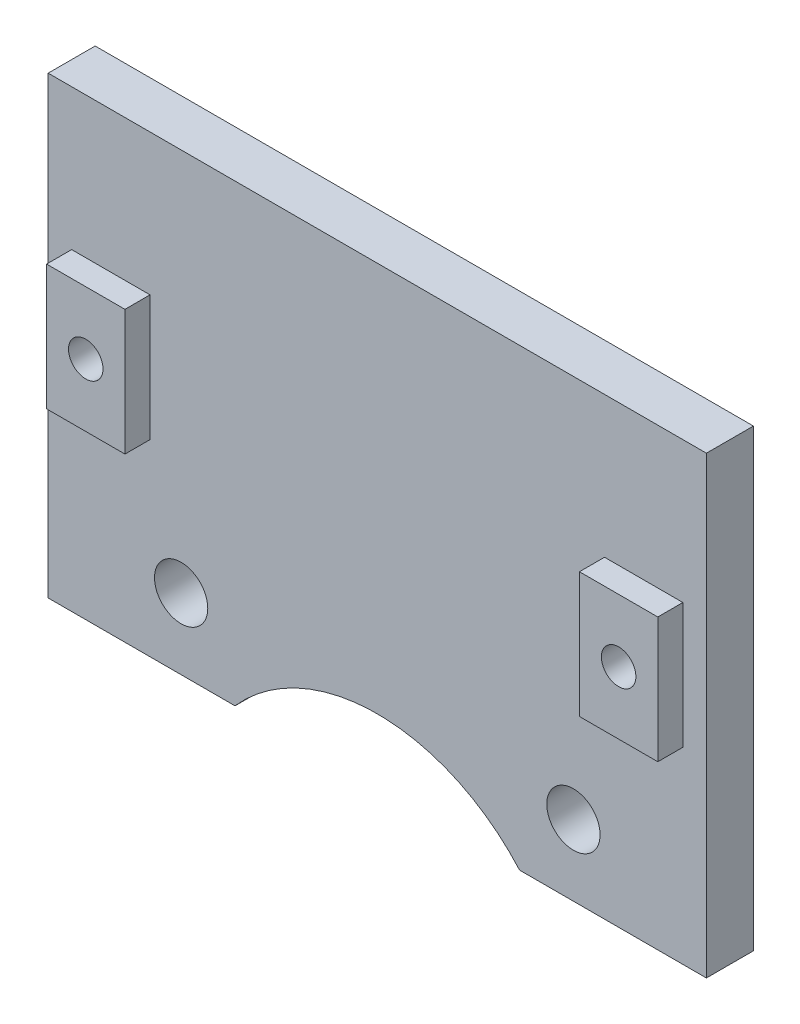
SolidWorks part; units mm, degrees
other "Carrier Accelerometer Bracket"
ref_plane "Front Plane" through (0, 0, 0) normal (0, 0, 1) x (1, 0, 0)
ref_plane "Top Plane" through (0, 0, 0) normal (0, 1, 0) x (1, 0, 0)
ref_plane "Right Plane" through (0, 0, 0) normal (1, 0, 0) x (0, 0, -1)
sketch3d "Mounting Plate Sketch datum points"
  point P0 (0, 0, 0)
  point P1 (10, 0, 0)
  point P2 (0, 10, 0)
ref_plane "Mounting Plate Sketch plane" through (0, 0, 0) normal (0, 0, 1) x (1, 0, 0)
sketch "Mounting Plate Sketch" plane through (0, 0, 0) normal (0, 0, 1) x (1, 0, 0)
  line L0 (-21, -16) -> (21, -16)
  line L1 (21, -16) -> (21, 13)
  line L2 (21, 13) -> (-21, 13)
  line L3 (-21, 13) -> (-21, -16)
extrude "Mounting Plate" add sketch "Mounting Plate Sketch" along normal blind 3 separate body
sketch3d "Axle Collar Clearance Sketch datum points"
  point P0 (0, 0, -0.1)
  point P1 (10, 0, -0.1)
  point P2 (0, 10, -0.1)
ref_plane "Axle Collar Clearance Sketch plane" through (0, 0, -0.1) normal (0, 0, 1) x (1, 0, 0)
sketch "Axle Collar Clearance Sketch" plane through (0, 0, -0.1) normal (0, 0, 1) x (1, 0, 0)
  circle A0 centre (0, -24) radius 12.1
extrude "Axle Collar Clearance" cut sketch "Axle Collar Clearance Sketch" along normal blind 3.2
sketch3d "M3 Cap Bolt Hole 1 Sketch datum points"
  point P0 (0, 0, -0.1)
  point P1 (10, 0, -0.1)
  point P2 (0, 10, -0.1)
ref_plane "M3 Cap Bolt Hole 1 Sketch plane" through (0, 0, -0.1) normal (0, 0, 1) x (1, 0, 0)
sketch "M3 Cap Bolt Hole 1 Sketch" plane through (0, 0, -0.1) normal (0, 0, 1) x (1, 0, 0)
  circle A0 centre (-12.5158, -11.4842) radius 1.7
extrude "M3 Cap Bolt Hole 1" cut sketch "M3 Cap Bolt Hole 1 Sketch" along normal blind 3.2
sketch3d "M3 Cap Bolt Hole 2 Sketch datum points"
  point P0 (0, 0, -0.1)
  point P1 (10, 0, -0.1)
  point P2 (0, 10, -0.1)
ref_plane "M3 Cap Bolt Hole 2 Sketch plane" through (0, 0, -0.1) normal (0, 0, 1) x (1, 0, 0)
sketch "M3 Cap Bolt Hole 2 Sketch" plane through (0, 0, -0.1) normal (0, 0, 1) x (1, 0, 0)
  circle A0 centre (12.5158, -11.4842) radius 1.7
extrude "M3 Cap Bolt Hole 2" cut sketch "M3 Cap Bolt Hole 2 Sketch" along normal blind 3.2
sketch3d "Clamp Seat 1 Sketch datum points"
  point P0 (0, 0, 2.9)
  point P1 (10, 0, 2.9)
  point P2 (0, 10, 2.9)
ref_plane "Clamp Seat 1 Sketch plane" through (0, 0, 2.9) normal (0, 0, 1) x (1, 0, 0)
sketch "Clamp Seat 1 Sketch" plane through (0, 0, 2.9) normal (0, 0, 1) x (1, 0, 0)
  line L0 (-19.5, -4) -> (-14.5, -4)
  line L1 (-14.5, -4) -> (-14.5, 4)
  line L2 (-14.5, 4) -> (-19.5, 4)
  line L3 (-19.5, 4) -> (-19.5, -4)
extrude "Clamp Seat 1" add sketch "Clamp Seat 1 Sketch" along normal blind 1.7
sketch3d "M2 Screw Clearance 1 Sketch datum points"
  point P0 (0, 0, -0.1)
  point P1 (10, 0, -0.1)
  point P2 (0, 10, -0.1)
ref_plane "M2 Screw Clearance 1 Sketch plane" through (0, 0, -0.1) normal (0, 0, 1) x (1, 0, 0)
sketch "M2 Screw Clearance 1 Sketch" plane through (0, 0, -0.1) normal (0, 0, 1) x (1, 0, 0)
  circle A0 centre (-17, 0) radius 1.1
extrude "M2 Screw Clearance 1" cut sketch "M2 Screw Clearance 1 Sketch" along normal blind 4.8
sketch3d "M2 Insert Pocket 1 Sketch datum points"
  point P0 (0, 0, -0.1)
  point P1 (10, 0, -0.1)
  point P2 (0, 10, -0.1)
ref_plane "M2 Insert Pocket 1 Sketch plane" through (0, 0, -0.1) normal (0, 0, 1) x (1, 0, 0)
sketch "M2 Insert Pocket 1 Sketch" plane through (0, 0, -0.1) normal (0, 0, 1) x (1, 0, 0)
  circle A0 centre (-17, 0) radius 1.6
extrude "M2 Insert Pocket 1" cut sketch "M2 Insert Pocket 1 Sketch" along normal blind 2.5
sketch3d "Clamp Seat 2 Sketch datum points"
  point P0 (0, 0, 2.9)
  point P1 (10, 0, 2.9)
  point P2 (0, 10, 2.9)
ref_plane "Clamp Seat 2 Sketch plane" through (0, 0, 2.9) normal (0, 0, 1) x (1, 0, 0)
sketch "Clamp Seat 2 Sketch" plane through (0, 0, 2.9) normal (0, 0, 1) x (1, 0, 0)
  line L0 (14.5, -4) -> (19.5, -4)
  line L1 (19.5, -4) -> (19.5, 4)
  line L2 (19.5, 4) -> (14.5, 4)
  line L3 (14.5, 4) -> (14.5, -4)
extrude "Clamp Seat 2" add sketch "Clamp Seat 2 Sketch" along normal blind 1.7
sketch3d "M2 Screw Clearance 2 Sketch datum points"
  point P0 (0, 0, -0.1)
  point P1 (10, 0, -0.1)
  point P2 (0, 10, -0.1)
ref_plane "M2 Screw Clearance 2 Sketch plane" through (0, 0, -0.1) normal (0, 0, 1) x (1, 0, 0)
sketch "M2 Screw Clearance 2 Sketch" plane through (0, 0, -0.1) normal (0, 0, 1) x (1, 0, 0)
  circle A0 centre (17, 0) radius 1.1
extrude "M2 Screw Clearance 2" cut sketch "M2 Screw Clearance 2 Sketch" along normal blind 4.8
sketch3d "M2 Insert Pocket 2 Sketch datum points"
  point P0 (0, 0, -0.1)
  point P1 (10, 0, -0.1)
  point P2 (0, 10, -0.1)
ref_plane "M2 Insert Pocket 2 Sketch plane" through (0, 0, -0.1) normal (0, 0, 1) x (1, 0, 0)
sketch "M2 Insert Pocket 2 Sketch" plane through (0, 0, -0.1) normal (0, 0, 1) x (1, 0, 0)
  circle A0 centre (17, 0) radius 1.6
extrude "M2 Insert Pocket 2" cut sketch "M2 Insert Pocket 2 Sketch" along normal blind 2.5
